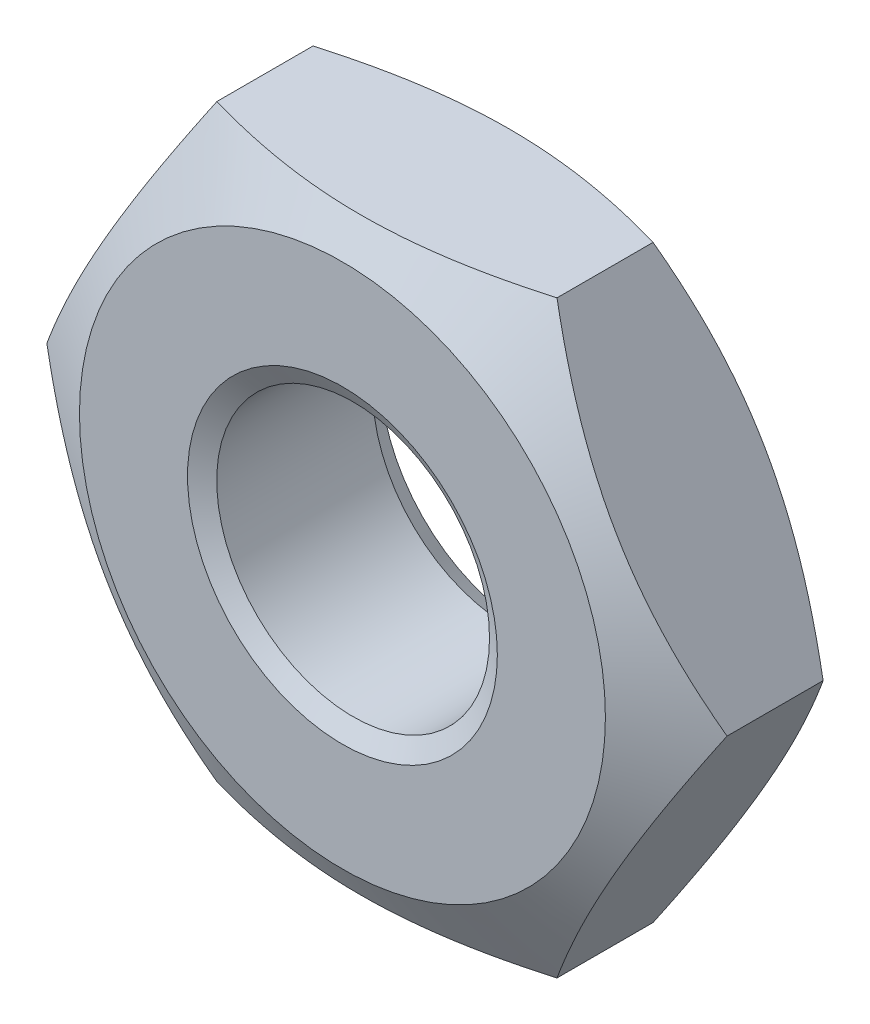
SolidWorks part; units mm, degrees
ref_plane "Front" through (0, 0, 0) normal (0, 0, 1) x (1, 0, 0)
ref_plane "Top" through (0, 0, 0) normal (0, 1, 0) x (1, 0, 0)
ref_plane "Right" through (0, 0, 0) normal (1, 0, 0) x (0, 0, -1)
other "Configuration Table"
sketch "Sketch1" plane through (0, 0, 0) normal (0, 0, 1) x (1, 0, 0)
  line L1 (2.0207, -3.5) -> (4.0415, 0)
  line L2 (4.0415, 0) -> (2.0207, 3.5)
  line L3 (2.0207, 3.5) -> (-2.0207, 3.5)
  line L4 (-2.0207, 3.5) -> (-4.0415, 0)
  line L5 (-4.0415, 0) -> (-2.0207, -3.5)
  line L6 (-2.0207, -3.5) -> (2.0207, -3.5)
  circle A0 centre (0, 0) radius 3.5 construction
  circle A1 centre (0, 0) radius 1.621
  dimension "D" = 3.242
  dimension "s" = 7
extrude "BaseNut" add sketch "Sketch1" against normal blind 2.2
cosmetic thread "ThreadCosmetic1" [suppressed] parameters "D"=4
sketch "Sketch2" plane through (0, 0, 0) normal (0, 1, 0) x (1, 0, 0)
  line L0 (-4.0415, 2.2) -> (-3.125, 2.2)
  line L2 (-3.125, 2.2) -> (-4.0415, 1.6709)
  line L3 (-4.0415, 1.6709) -> (-4.0415, 2.2)
  line L4 (0, 3.3759) -> (0, -9.8171) construction
  line L6 (-9.7712, 1.1) -> (9.8853, 1.1) construction
  line L7 (-4.0415, 0.5291) -> (-4.0415, 0)
  line L8 (-3.125, 0) -> (-4.0415, 0.5291)
  line L9 (-4.0415, 0) -> (-3.125, 0)
  dimension "dw" = 6.25
  dimension "D1" = 30
  dimension "D2" = 1.1
revolve "Double-Chamfer" cut sketch "Sketch2" angle 360 about L4
chamfer "EndChamfer" distance 0.22 angle 30 2 edges at (1.621, 0, -2.2) (1.621, 0, 0)
sketch "Sketch3" plane through (0, 0, 0) normal (0, 1, 0) x (1, 0, 0)
  line L0 (0, 6.7075) -> (0, -2.1252) construction
  line L1 (1.242, 2.1695) -> (1.621, 2.1695)
  line L2 (1.621, 2.1695) -> (1.9492, 1.98)
  line L3 (1.9492, 1.98) -> (1.621, 1.7905)
  line L4 (1.621, 1.7905) -> (1.242, 1.7905)
  line L5 (1.242, 1.7905) -> (1.242, 2.1695)
  line L6 (1.621, 1.98) -> (-1.621, 1.98) construction
  dimension "D1" = 0.379
  dimension "D2" = 3.242
revolve "Cut-Revolve10" [suppressed] cut sketch "Sketch3" angle 360 about L0
pattern_linear "LPattern10" [suppressed] count 4 spacing 0.4548 along (0, 0, 1)
equation "\"dw@Sketch2\" = \"s@Sketch1\"-0.75"
equation "\"D2@Sketch2\" = \"m@BaseNut\" / 2"
equation "\"D1@EndChamfer\" = \"m@BaseNut\" / 10"
equation "\"D2@Sketch3\" = \"D@Sketch1\""
equation "\"D1@Sketch3\" = (  \"D@ThreadCosmetic1\" - \"D@Sketch1\" )  / 2"
equation "\"D3@LPattern10\" = \"D1@Sketch3\" * 1.2"
equation "\"D1@LPattern10\" = (  \"m@BaseNut\" - \"D1@EndChamfer\" )  / \"D3@LPattern10\" "
